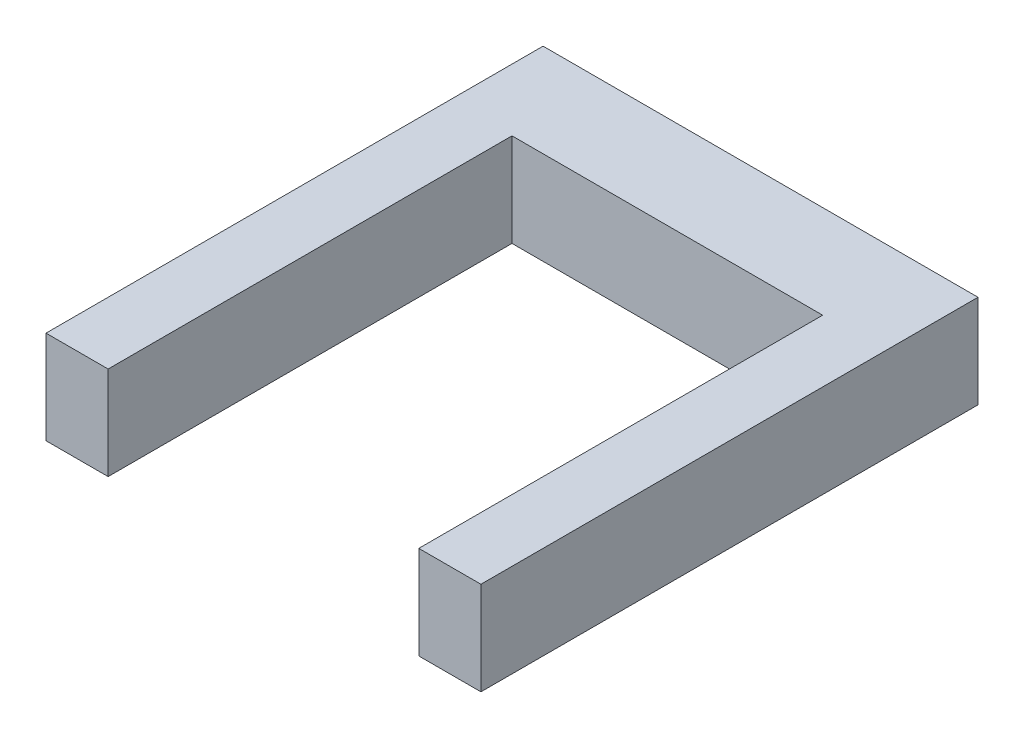
SolidWorks part; units mm, degrees
ref_plane "Front Plane" through (0, 0, 0) normal (0, 0, 1) x (1, 0, 0)
ref_plane "Top Plane" through (0, 0, 0) normal (0, 1, 0) x (1, 0, 0)
ref_plane "Right Plane" through (0, 0, 0) normal (1, 0, 0) x (0, 0, -1)
sketch "Sketch1" plane through (0, 0, 0) normal (0, 1, 0) x (1, 0, 0)
  line L0 (0, 406.4) -> (0, -406.4) construction
  line L1 (-355.6, 406.4) -> (355.6, 406.4)
  line L2 (-355.6, 406.4) -> (-355.6, -406.4)
  line L3 (-355.6, -406.4) -> (355.6, -406.4)
  line L4 (355.6, 406.4) -> (355.6, -406.4)
  point P6 (0, 0)
  dimension "D1" = 812.8
  dimension "D2" = 711.2
extrude "Boss-Extrude1" add sketch "Sketch1" along normal blind 152.4
sketch "Sketch2" plane through (0, 152.4, 0) normal (0, 1, 0) x (1, 0, 0)
  line L0 (355.6, 406.4) -> (-355.6, 406.4) construction
  line L1 (-254, 406.4) -> (254, 406.4)
  line L2 (-254, 406.4) -> (-254, 152.4)
  line L3 (-254, 152.4) -> (254, 152.4)
  line L4 (254, 406.4) -> (254, 152.4)
  line L5 (0, 152.4) -> (0, 0) construction
  line L6 (355.6, -406.4) -> (355.6, 406.4) construction
  dimension "D1" = 254
  dimension "D2" = 101.6
extrude "Cut-Extrude1" [suppressed] cut sketch "Sketch2" against normal through all
chamfer "Chamfer1" [suppressed] distance 101.6 angle 45
sketch "Sketch3" plane through (0, 152.4, 0) normal (0, 1, 0) x (1, 0, 0)
  line L0 (-355.6, -406.4) -> (355.6, -406.4) construction
  line L1 (-254, -406.4) -> (254, -406.4)
  line L2 (-254, -406.4) -> (-254, 254)
  line L3 (-254, 254) -> (254, 254)
  line L4 (254, -406.4) -> (254, 254)
  line L5 (-355.6, 406.4) -> (-355.6, -406.4) construction
  line L6 (355.6, 406.4) -> (-355.6, 406.4) construction
  point P6 (0, -406.4)
  dimension "D1" = 101.6
  dimension "D2" = 152.4
extrude "Cut-Extrude2" cut sketch "Sketch3" against normal through all
